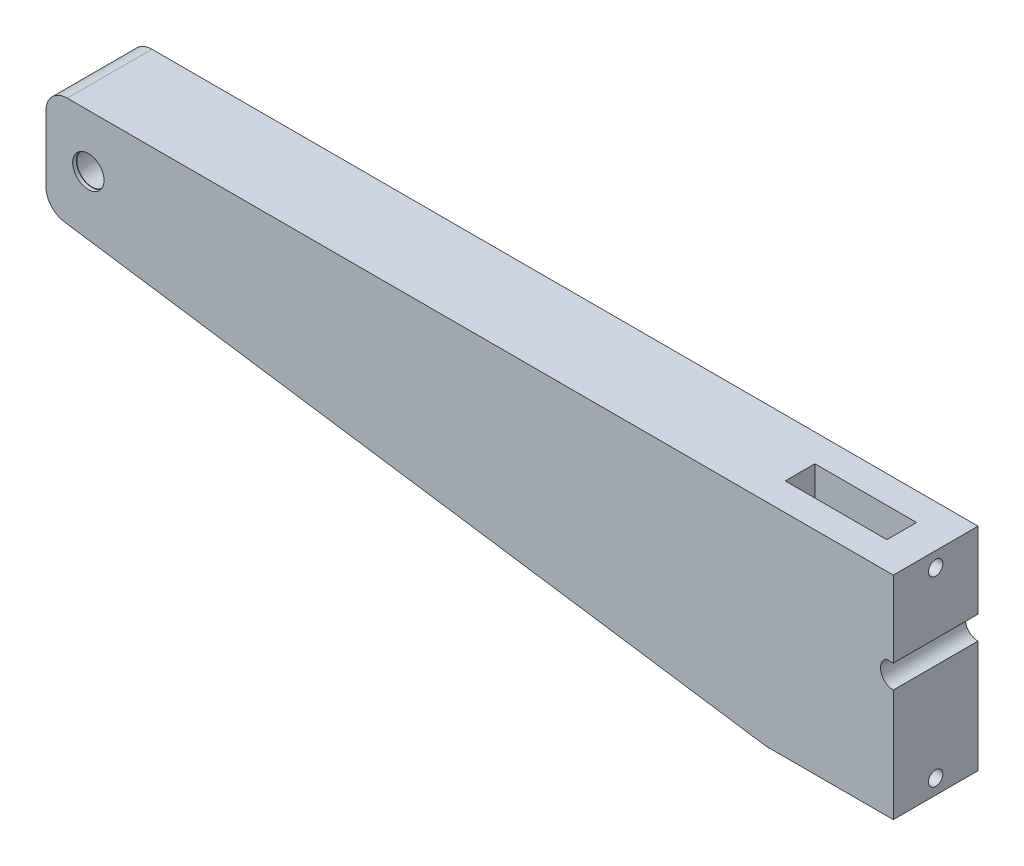
SolidWorks part; units mm, degrees
ref_plane "Front Plane" through (0, 0, 0) normal (0, 0, 1) x (1, 0, 0)
ref_plane "Top Plane" through (0, 0, 0) normal (0, 1, 0) x (1, 0, 0)
ref_plane "Right Plane" through (0, 0, 0) normal (1, 0, 0) x (0, 0, -1)
other "Center of Mass"
sketch "Sketch1" plane through (0, 0, 0) normal (0, 0, 1) x (1, 0, 0)
  line L0 (-30, 0) -> (0, 0)
  line L1 (-30, 0) -> (-200, 25)
  line L2 (-200, 25) -> (-200, 50)
  line L5 (200, 50) -> (200, 25)
  line L8 (0, 50) -> (0, 32.5)
  line L10 (190, 37.5) -> (200, 37.5) construction
  line L11 (-190, 37.5) -> (-200, 37.5) construction
  line L12 (-200, 50) -> (0, 50)
  line L13 (0, 26.5) -> (0, 0)
  line L14 (-1.6583, 32) -> (0, 32)
  line L15 (0, 32) -> (0, 32.5)
  arc A0 (-1.6583, 32) -> (0, 26.5) centre (0, 29.5) ccw
  circle A5 centre (-190, 37.5) radius 3.575
  circle A6 centre (190, 37.5) radius 3.575
  point P15 (200, 37.5)
  dimension "D6" = 6
  dimension "D9" = 3
  dimension "D8" = 7.15
  dimension "D1" = 200
  dimension "D2" = 30
  dimension "D3" = 25
  dimension "D4" = 50
  dimension "D5" = 5.5
  dimension "D7" = 10
  dimension "D10" = 26.5
extrude "Boss-Extrude1" add sketch "Sketch1" along normal blind 20
fillet "Fillet1" radius 5 2 edges at (-200, 25, 10) (-200, 50, 10)
sketch "Sketch3" plane through (0, 0, 20) normal (0, 0, 1) x (1, 0, 0)
  circle A0 centre (-190, 37.5) radius 3.7
  point P6 (0, 0)
  dimension "D1" = 7.4
sketch "Sketch5" plane through (0, 50, 0) normal (0, 1, 0) x (1, 0, 0)
  line L0 (0, -20) -> (0, 0) construction
  line L1 (-8, -6.5) -> (-32, -6.5)
  line L2 (-8, -6.5) -> (-8, -13.5)
  line L3 (-8, -13.5) -> (-32, -13.5)
  line L4 (-32, -6.5) -> (-32, -13.5)
  point P6 (-8, -10)
  point P7 (0, -10)
  dimension "D1" = 8
  dimension "D2" = 7
  dimension "D3" = 24
extrude "Cut-Extrude1" cut sketch "Sketch5" against normal blind 7
sketch "Sketch6" plane through (-8, 0, 0) normal (-1, 0, 0) x (0, 0, 1)
  line L0 (13.5, 43) -> (6.5, 43) construction
  line L1 (6.5, 43) -> (6.5, 50) construction
  circle A0 centre (10, 46.5) radius 1.7
  point P4 (10, 43)
  point P7 (6.5, 46.5)
  dimension "D1" = 3.4
extrude "Cut-Extrude2" cut sketch "Sketch6" against normal up to surface (8 mm away) up to face at (0, 41, 10)
ref_plane "Plane1" through (0, 25, 0) normal (0, 1, 0) x (1, 0, 0)
mirror "Mirror1" about plane through (0, 25, 0) normal (0, 1, 0) of "Cut-Extrude2", "Cut-Extrude1"
extrude "Cut-Extrude3" cut sketch "Sketch3" against normal blind 0.85
ref_plane "Plane2" through (0, 0, 10) normal (0, 0, 1) x (1, 0, 0)
mirror "Mirror2" about plane through (0, 0, 10) normal (0, 0, 1) of "Cut-Extrude3"
